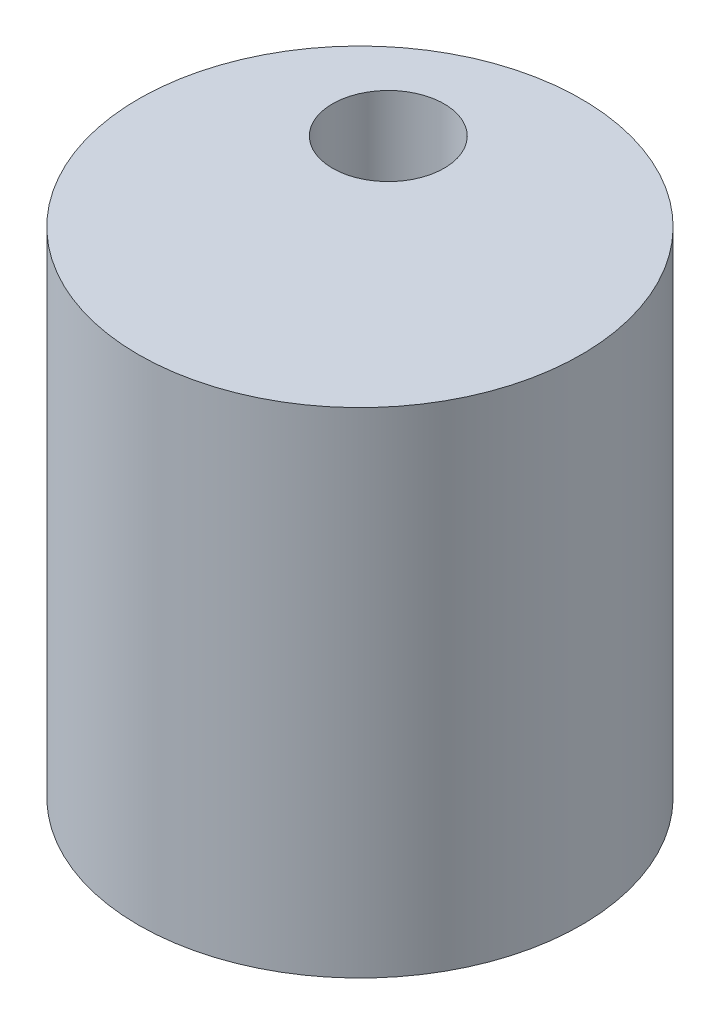
SolidWorks part; units mm, degrees
material "ABS PC"
ref_plane "X-Y Datum" through (0, 0, 0) normal (0, 0, 1) x (1, 0, 0)
ref_plane "X-Z Datum" through (0, 0, 0) normal (0, 1, 0) x (1, 0, 0)
ref_plane "Y-Z Datum" through (0, 0, 0) normal (1, 0, 0) x (0, 0, -1)
sketch "Sketch1" plane through (0, 0, 0) normal (0, 1, 0) x (1, 0, 0)
  line L0 (0, 0) -> (0, 5.4864) construction
  line L1 (0, 5.4864) -> (-3.81, 5.4864) construction
  circle A1 centre (0, 0) radius 13.0937
  circle A4 centre (-3.81, 5.4864) radius 3.302
  dimension "D1" = 26.1874
  dimension "D2" = 3.81
  dimension "D4" = 6.604
  dimension "D3" = 5.4864
extrude "Boss-Extrude1" add sketch "Sketch1" against normal blind 29.21
